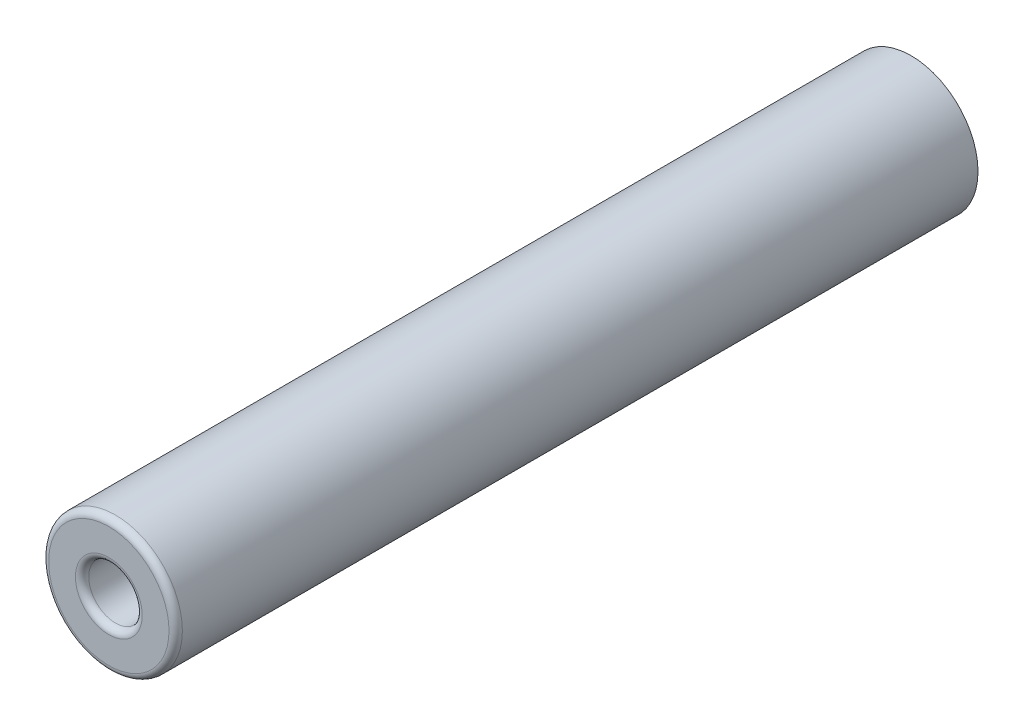
SolidWorks part; units mm, degrees
material "Acero aleado"
ref_plane "Alzado" through (0, 0, 0) normal (0, 0, 1) x (1, 0, 0)
ref_plane "Planta" through (0, 0, 0) normal (0, 1, 0) x (1, 0, 0)
ref_plane "Vista lateral" through (0, 0, 0) normal (1, 0, 0) x (0, 0, -1)
sketch "Croquis1" plane through (0, 0, 0) normal (0, 0, 1) x (1, 0, 0)
  circle A0 centre (0, 0) radius 2.5
  dimension "D1" = 5
extrude "Saliente-Extruir1" add sketch "Croquis1" along normal blind 30
sketch "Croquis2" plane through (0, 0, 30) normal (0, 0, 1) x (1, 0, 0)
  circle A0 centre (0, 0) radius 1
  dimension "D1" = 2
extrude "Cortar-Extruir1" cut sketch "Croquis2" against normal blind 10
fillet "Redondeo1" radius 0.25 2 edges at (2.5, 0, 30) (1, 0, 30)
sketch "Sketch1" plane through (0, 0, 30) normal (0, 0, 1) x (1, 0, 0)
  line L0 (0, 0) -> (0, 24.5) construction
  dimension "D1" = 24.5
